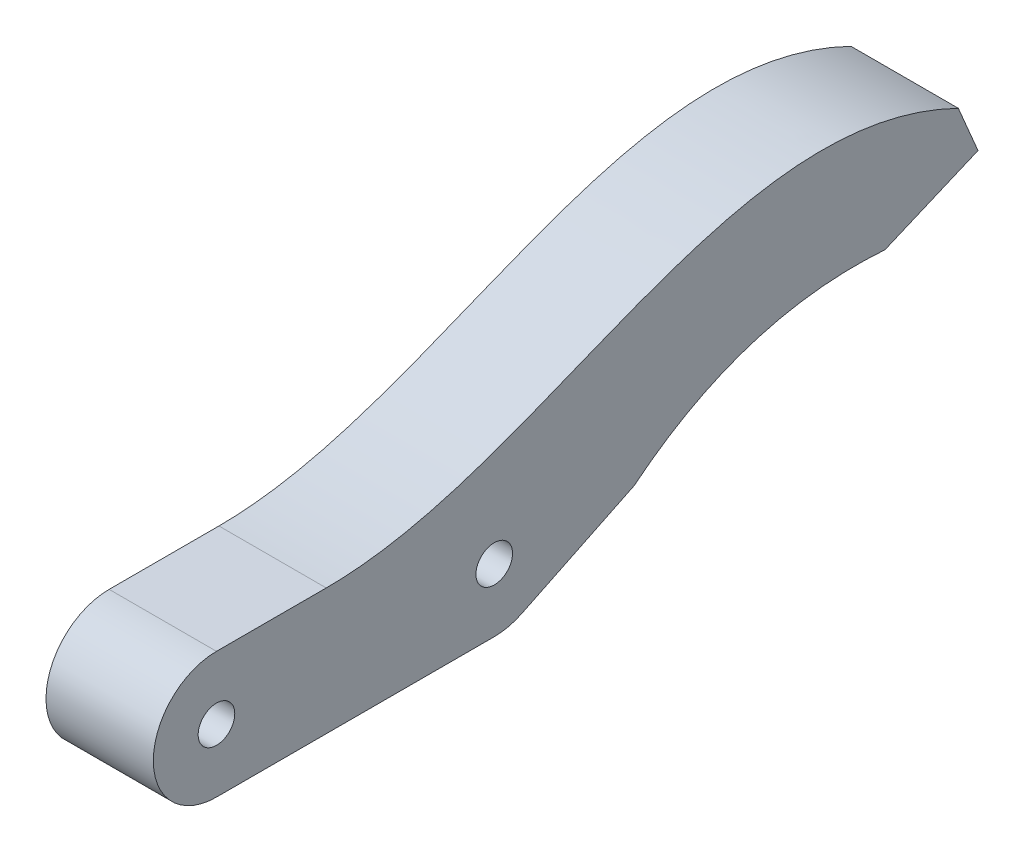
SolidWorks part; units mm, degrees
ref_plane "Front Plane" through (0, 0, 0) normal (0, 0, 1) x (1, 0, 0)
ref_plane "Top Plane" through (0, 0, 0) normal (0, 1, 0) x (1, 0, 0)
ref_plane "Right Plane" through (0, 0, 0) normal (1, 0, 0) x (0, 0, -1)
sketch "Sketch1" plane through (0, 0, 0) normal (1, 0, 0) x (0, 0, -1)
  line L1 (0, 0) -> (27, 0)
  line L2 (0, 0) -> (0, 10)
  line L3 (0, 10) -> (27, 10)
  circle A0 centre (5, 5) radius 1.45
  circle A1 centre (5, 5) radius 5
  circle A2 centre (27, 5) radius 5
  circle A3 centre (27, 5) radius 1.45
  dimension "D7" = 2.9
  dimension "D11" = 10
  dimension "D2" = 2.9
  dimension "D1" = 10
  dimension "D8" = 5
  dimension "D9" = 5
  dimension "D10" = 22
extrude "Boss-Extrude1" add sketch "Sketch1" along normal blind 8.5 contours A1 A0 | A2 L3 A1 L1 | A2 A3 | L2 A1 | L1 A1
sketch "Sketch2" plane through (8.5, 0, 0) normal (1, 0, 0) x (0, 0, -1)
  line L6 (5, 10) -> (27, 10) construction
  line L14 (5, 10) -> (27, 10)
  line L20 (29.1838, 0.5021) -> (38.0854, 4.8241)
  line L21 (57.948, 11.0678) -> (65.3138, 14.1895)
  line L22 (65.3138, 14.1895) -> (63.753, 17.8724)
  arc A3 (27, 0) -> (27, 10) centre (27, 5) ccw construction
  arc A4 (27, 0) -> (27, 10) centre (27, 5) ccw
  spline S0 degree 2 poles (38.0854, 4.8241) (46.7975, 11.8952) (57.948, 11.0678) knots 0 0 0 1 1 1
  spline S1 degree 3 poles (63.753, 17.8724) (45.9289, 26.5638) (31.0593, 10) (13.695, 10) knots 0 0 0 0 1 1 1 1
  point P2 (27, 5)
  dimension "D3" = 4
  dimension "D4" = 8
extrude "Boss-Extrude2" add sketch "Sketch2" against normal blind 8.5
